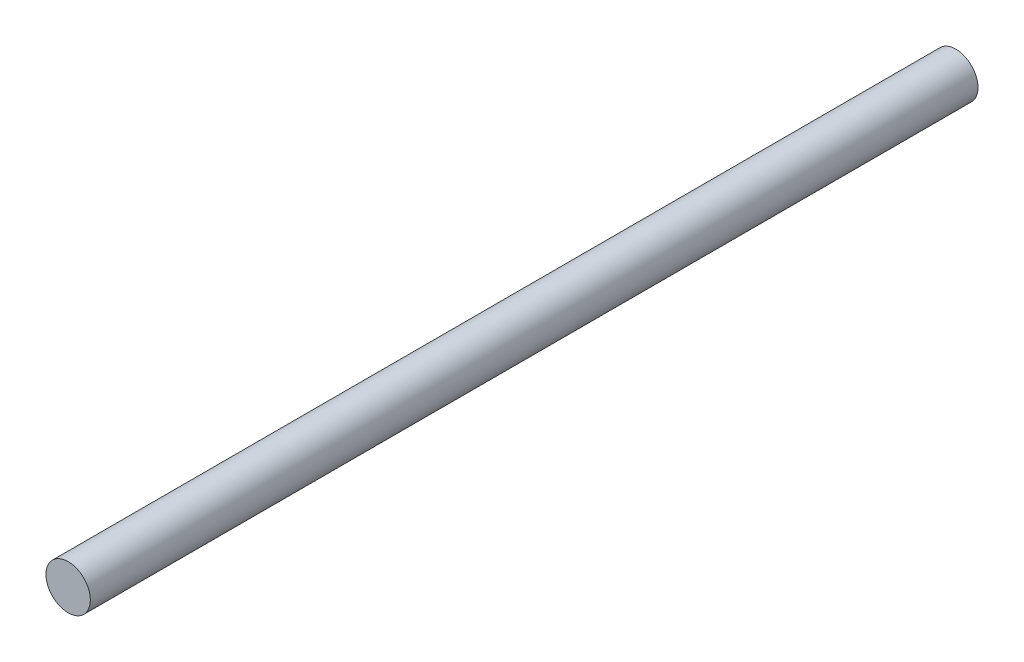
SolidWorks part; units mm, degrees
material "6061 Alloy"
ref_plane "Front Plane" through (0, 0, 0) normal (0, 0, 1) x (1, 0, 0)
ref_plane "Top Plane" through (0, 0, 0) normal (0, 1, 0) x (1, 0, 0)
ref_plane "Right Plane" through (0, 0, 0) normal (1, 0, 0) x (0, 0, -1)
sketch "Sketch1" plane through (0, 0, 0) normal (0, 0, 1) x (1, 0, 0)
  circle A0 centre (0, 0) radius 3.175
  dimension "D1" = 6.35
extrude "Boss-Extrude1" add sketch "Sketch1" along normal blind 127 contours A0
